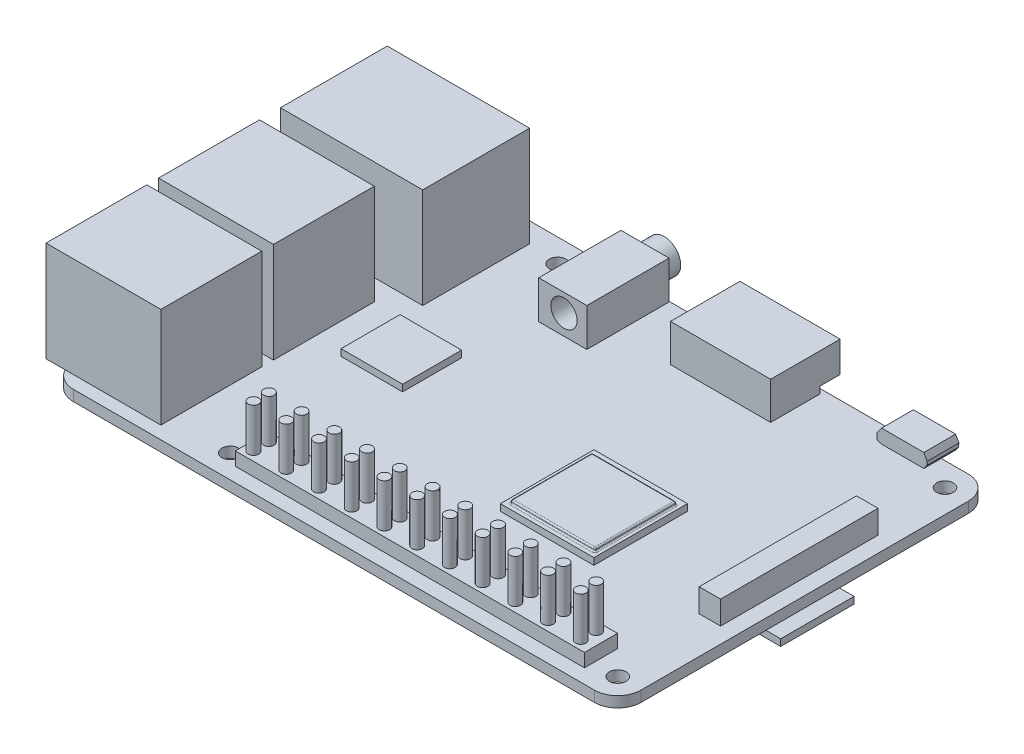
SolidWorks part; units mm, degrees
ref_plane "Front Plane" through (0, 0, 0) normal (0, 0, 1) x (1, 0, 0)
ref_plane "Top Plane" through (0, 0, 0) normal (0, 1, 0) x (1, 0, 0)
ref_plane "Right Plane" through (0, 0, 0) normal (1, 0, 0) x (0, 0, -1)
sketch "Sketch1" plane through (0, 0, 0) normal (0, 1, 0) x (1, 0, 0)
  line L1 (0, 0) -> (85, 0)
  line L2 (0, 0) -> (0, 56)
  line L3 (0, 56) -> (85, 56)
  line L4 (85, 0) -> (85, 56)
  dimension "D1" = 56
  dimension "D2" = 85
extrude "Boss-Extrude1" add sketch "Sketch1" along normal blind 1.6
fillet "Fillet1" radius 3.5 4 edges at (85, 0.8, -56) (85, 0.8, 0) (0, 0.8, 0) (0, 0.8, -56)
sketch "Sketch2" plane through (0, 1.6, 0) normal (0, 1, 0) x (1, 0, 0)
  line L1 (18.8, 53.0063) -> (-2.5, 53.0063)
  line L2 (18.8, 53.0063) -> (18.8, 37.0063)
  line L3 (18.8, 37.0063) -> (-2.5, 37.0063)
  line L4 (-2.5, 53.0063) -> (-2.5, 37.0063)
  line L5 (14.7, 33.8663) -> (-2.5, 33.8663)
  line L6 (14.7, 33.8663) -> (14.7, 18.7663)
  line L7 (14.7, 18.7663) -> (-2.5, 18.7663)
  line L8 (-2.5, 33.8663) -> (-2.5, 18.7663)
  line L9 (14.7, 17.0126) -> (-2.5, 17.0126)
  line L10 (14.7, 17.0126) -> (14.7, 1.9126)
  line L11 (14.7, 1.9126) -> (-2.5, 1.9126)
  line L12 (-2.5, 17.0126) -> (-2.5, 1.9126)
  line L13 (0, 52.5) -> (0, 3.5) construction
  point P12 (9.2217, 37.0063)
  point P13 (9.3042, 1.9126)
  dimension "D1" = 16
  dimension "D2" = 3.14
  dimension "D3" = 15.1
  dimension "D4" = 15.1
  dimension "D5" = 2.5
  dimension "D6" = 2.5
  dimension "D7" = 2.5
  dimension "D8" = 21.3
  dimension "D9" = 17.2
  dimension "D10" = 17.2
extrude "Boss-Extrude2" add sketch "Sketch2" along normal blind 15
sketch "Sketch3" plane through (-2.5, 0, 0) normal (-1, 0, 0) x (0, 0, 1)
  line L0 (-45.8667, 4.3384) -> (-51.1516, 4.3384)
  line L1 (-51.1516, 14.7961) -> (-38.5002, 14.7961)
  line L2 (-51.1516, 14.7961) -> (-51.1516, 4.3384)
  line L3 (-43.0569, 4.3384) -> (-38.5002, 4.3384)
  line L4 (-38.5002, 14.7961) -> (-38.5002, 4.3384)
  line L6 (-45.8667, 4.3384) -> (-45.8667, 3.5056)
  line L7 (-45.8667, 3.5056) -> (-43.0569, 3.5056)
  line L8 (-43.0569, 4.3384) -> (-43.0569, 3.5056)
extrude "Cut-Extrude1" cut sketch "Sketch3" against normal blind 12
sketch "Sketch4" plane through (-2.5, 0, 0) normal (-1, 0, 0) x (0, 0, 1)
  line L1 (-32.1262, 7.3198) -> (-20.7974, 7.3198)
  line L2 (-32.1262, 7.3198) -> (-32.1262, 3.1429)
  line L3 (-32.1262, 3.1429) -> (-20.7974, 3.1429)
  line L4 (-20.7974, 7.3198) -> (-20.7974, 3.1429)
  line L5 (-32.0153, 14.7191) -> (-20.7974, 14.7191)
  line L6 (-32.0153, 14.7191) -> (-32.0153, 10.2087)
  line L7 (-32.0153, 10.2087) -> (-20.7974, 10.2087)
  line L8 (-20.7974, 14.7191) -> (-20.7974, 10.2087)
  line L9 (-14.8393, 14.7191) -> (-3.9221, 14.7191)
  line L10 (-14.8393, 14.7191) -> (-14.8393, 10.2087)
  line L11 (-14.8393, 10.2087) -> (-3.9221, 10.2087)
  line L12 (-3.9221, 14.7191) -> (-3.9221, 10.2087)
  line L13 (-14.5764, 7.3198) -> (-3.9221, 7.3198)
  line L14 (-14.5764, 7.3198) -> (-14.5764, 3.1429)
  line L15 (-14.5764, 3.1429) -> (-3.9221, 3.1429)
  line L16 (-3.9221, 7.3198) -> (-3.9221, 3.1429)
  point P16 (-32.0153, 14.7191)
  point P17 (-14.929, 14.8896)
  point P18 (-14.8393, 14.7191)
  point P19 (-3.9221, 7.3198)
  point P20 (-20.7974, 7.3198)
extrude "Cut-Extrude2" cut sketch "Sketch4" against normal blind 12
sketch "Sketch5" plane through (0, 1.6, 0) normal (0, 1, 0) x (1, 0, 0)
  line L1 (19.274, 33.143) -> (28.4891, 33.143)
  line L2 (19.274, 33.143) -> (19.274, 24.3088)
  line L3 (19.274, 24.3088) -> (28.4891, 24.3088)
  line L4 (28.4891, 33.143) -> (28.4891, 24.3088)
extrude "Boss-Extrude3" add sketch "Sketch5" along normal blind 1
sketch "Sketch6" plane through (0, 1.6, 0) normal (0, 1, 0) x (1, 0, 0)
  line L0 (85, 3.5) -> (85, 52.5) construction
  line L1 (60, 47.9) -> (45, 47.9)
  line L2 (60, 47.9) -> (60, 58.3)
  line L3 (60, 58.3) -> (45, 58.3)
  line L4 (45, 47.9) -> (45, 58.3)
  line L5 (81.5, 56) -> (3.5, 56) construction
  dimension "D1" = 40
  dimension "D2" = 15
  dimension "D3" = 2.3
  dimension "D4" = 10.4
extrude "Boss-Extrude4" add sketch "Sketch6" along normal blind 5.6
sketch "Sketch8" plane through (0, 1.6, 0) normal (0, 1, 0) x (1, 0, 0)
  line L1 (51.3008, 30.1415) -> (65.3008, 30.1415)
  line L2 (51.3008, 30.1415) -> (51.3008, 16.1415)
  line L3 (51.3008, 16.1415) -> (65.3008, 16.1415)
  line L4 (65.3008, 30.1415) -> (65.3008, 16.1415)
  dimension "D1" = 14
  dimension "D2" = 14
extrude "Boss-Extrude5" add sketch "Sketch8" along normal blind 1
sketch "Sketch9" plane through (0, 0, -58.3) normal (0, 0, -1) x (-1, 0, 0)
  line L0 (-60, 1.6) -> (-45, 1.6)
  line L1 (-60, 1.6) -> (-45, 1.6) construction
  line L2 (-45, 1.6) -> (-45, 2.6627)
  line L3 (-45, 7.2) -> (-45, 1.6) construction
  line L4 (-45, 2.6627) -> (-45.5313, 2.1313)
  line L5 (-45.5313, 2.1313) -> (-59.5164, 2.1313)
  line L6 (-59.5164, 2.1313) -> (-60, 2.615)
  line L7 (-60, 7.2) -> (-60, 1.6) construction
  line L8 (-60, 2.615) -> (-60, 1.6)
extrude "Cut-Extrude5" cut sketch "Sketch9" against normal blind 3
sketch "Sketch10" plane through (0, 0, -58.3) normal (0, 0, -1) x (-1, 0, 0)
  line L0 (-59.6001, 6.695) -> (-45.3941, 6.695)
  line L1 (-45.3941, 6.695) -> (-45.3941, 2.9073)
  line L2 (-45.3941, 2.9073) -> (-45.8714, 2.43)
  line L3 (-45.8714, 2.43) -> (-59.1227, 2.43)
  line L4 (-59.1227, 2.43) -> (-59.6001, 2.9073)
  line L5 (-59.6001, 2.9073) -> (-59.6001, 6.695)
  point P2 (0, 0)
extrude "Cut-Extrude6" cut sketch "Sketch10" against normal blind 8
sketch "Sketch11" plane through (0, 0, -50.3) normal (0, 0, -1) x (-1, 0, 0)
  line L1 (-58.676, 5.361) -> (-46.2488, 5.361)
  line L2 (-58.676, 5.361) -> (-58.676, 4.1859)
  line L3 (-58.676, 4.1859) -> (-46.2488, 4.1859)
  line L4 (-46.2488, 5.361) -> (-46.2488, 4.1859)
  point P4 (-46.2488, 5.361)
  point P5 (0, 0)
extrude "Boss-Extrude6" add sketch "Sketch11" along normal blind 8
sketch "Sketch12" plane through (0, 2.6, 0) normal (0, 1, 0) x (1, 0, 0)
  line L1 (64.6535, 16.9241) -> (52.0403, 16.9241)
  line L2 (64.6535, 16.9241) -> (64.6535, 29.11)
  line L3 (64.6535, 29.11) -> (52.0403, 29.11)
  line L4 (52.0403, 16.9241) -> (52.0403, 29.11)
  point P4 (64.6393, 29.3773)
  point P5 (0, 0)
  point P6 (64.2875, 16.9241)
  point P7 (0, 0)
  point P8 (64.6535, 29.11)
extrude "Boss-Extrude7" add sketch "Sketch12" along normal blind 0.5
fillet "Fillet3" radius 0.2 12 edges at (64.6535, 2.6, -23.017) (64.6535, 2.85, -29.11) (58.3469, 2.6, -29.11) (52.0403, 2.85, -29.11) (52.0403, 2.6, -23.017) (52.0403, 2.85, -16.9241) (64.6535, 2.85, -16.9241) (58.3469, 2.6, -16.9241) (58.3469, 3.1, -16.9241) (52.0403, 3.1, -23.017) (58.3469, 3.1, -29.11) (64.6535, 3.1, -23.017)
sketch "Sketch13" plane through (0, 1.6, 0) normal (0, 1, 0) x (1, 0, 0)
  line L0 (85, 3.5) -> (85, 52.5) construction
  line L1 (78.3, 53.2419) -> (70.5, 53.2419)
  line L2 (78.3, 53.2419) -> (78.3, 58)
  line L3 (78.3, 58) -> (70.5, 58)
  line L4 (70.5, 53.2419) -> (70.5, 58)
  line L5 (81.5, 56) -> (3.5, 56) construction
  dimension "D1" = 7.8
  dimension "D2" = 14.5
  dimension "D3" = 2
extrude "Boss-Extrude8" add sketch "Sketch13" along normal blind 2.5
sketch "Sketch14" plane through (0, 0, -58) normal (0, 0, -1) x (-1, 0, 0)
  line L0 (-78.0828, 2.9313) -> (-77.5883, 3.8329)
  line L1 (-77.5883, 3.8329) -> (-71.2708, 3.8329)
  line L2 (-71.2708, 3.8329) -> (-70.6143, 2.9313)
  line L3 (-70.6143, 2.9313) -> (-70.6143, 1.9851)
  line L4 (-70.6143, 1.9851) -> (-71.2708, 1.7507)
  line L5 (-71.2708, 1.7507) -> (-77.5883, 1.7507)
  line L6 (-77.5883, 1.7507) -> (-78.0171, 2.3396)
  line L7 (-78.0171, 2.3396) -> (-78.0828, 2.9313)
  line L8 (-78.3, 4.1) -> (-70.5, 4.1)
  line L9 (-70.5, 4.1) -> (-70.5, 1.6)
  line L10 (-70.5, 1.6) -> (-78.3, 1.6)
  line L11 (-78.3, 1.6) -> (-78.3, 4.1)
extrude "Cut-Extrude7" cut sketch "Sketch14" against normal up to next
sketch "Sketch15" plane through (0, 0, -58) normal (0, 0, -1) x (-1, 0, 0)
  line L1 (-77.2141, 3.1124) -> (-71.4762, 3.1124)
  line L2 (-77.2141, 3.1124) -> (-77.2141, 2.2105)
  line L3 (-77.2141, 2.2105) -> (-71.4762, 2.2105)
  line L4 (-71.4762, 3.1124) -> (-71.4762, 2.2105)
extrude "Cut-Extrude8" cut sketch "Sketch15" against normal blind 2.5
sketch "Sketch16" plane through (0, 0, 0) normal (0, -1, 0) x (1, 0, 0)
  line L0 (85, -3.5) -> (85, -52.5) construction
  line L1 (78.3416, -33.2) -> (87.2, -33.2)
  line L2 (78.3416, -33.2) -> (78.3416, -22.2)
  line L3 (78.3416, -22.2) -> (87.2, -22.2)
  line L4 (87.2, -33.2) -> (87.2, -22.2)
  line L5 (81.5, -56) -> (3.5, -56) construction
  dimension "D1" = 11
  dimension "D2" = 2.2
  dimension "D3" = 33.8
extrude "Boss-Extrude9" add sketch "Sketch16" along normal blind 1
sketch "Sketch17" plane through (0, 1.6, 0) normal (0, 1, 0) x (1, 0, 0)
  line L0 (81.5, 56) -> (3.5, 56) construction
  line L1 (36.7809, 43.6) -> (29.5809, 43.6)
  line L2 (36.7809, 43.6) -> (36.7809, 58.6)
  line L3 (36.7809, 58.6) -> (29.5809, 58.6)
  line L4 (29.5809, 43.6) -> (29.5809, 58.6)
  dimension "D1" = 7.2
  dimension "D2" = 15
  dimension "D3" = 2.6
extrude "Boss-Extrude10" add sketch "Sketch17" along normal blind 5.7
sketch "Sketch18" plane through (0, 0, -58.6) normal (0, 0, -1) x (-1, 0, 0)
  line L1 (-36.7809, 7.3) -> (-29.5809, 7.3)
  line L2 (-36.7809, 7.3) -> (-36.7809, 1.6)
  line L3 (-36.7809, 1.6) -> (-29.5809, 1.6)
  line L4 (-29.5809, 7.3) -> (-29.5809, 1.6)
  circle A0 centre (-33.3518, 4.5516) radius 2.4837
  point P8 (-33.2776, 4.8438)
  point P9 (-33.3518, 4.5516)
extrude "Cut-Extrude9" cut sketch "Sketch18" against normal blind 2.7
sketch "Sketch19" plane through (0, 0, -58.6) normal (0, 0, -1) x (-1, 0, 0)
  circle A0 centre (-33.3539, 4.6108) radius 1.9717
  point P2 (-33.3539, 4.6108)
extrude "Cut-Extrude10" cut sketch "Sketch19" against normal blind 15
sketch "Sketch20" plane through (0, 1.6, 0) normal (0, 1, 0) x (1, 0, 0)
  line L1 (79.4418, 17.7484) -> (82.658, 17.7484)
  line L2 (79.4418, 17.7484) -> (79.4418, 41.3101)
  line L3 (79.4418, 41.3101) -> (82.658, 41.3101)
  line L4 (82.658, 17.7484) -> (82.658, 41.3101)
  point P4 (82.658, 41.3101)
  point P6 (85, 40.4192)
  point P7 (79.4418, 41.7266)
  point P8 (0, 0)
extrude "Boss-Extrude11" add sketch "Sketch20" along normal blind 3.5
sketch "Sketch21" plane through (0, 1.6, 0) normal (0, 1, 0) x (1, 0, 0)
  line L1 (25.6119, 7.0948) -> (77.877, 7.0948)
  line L2 (25.6119, 7.0948) -> (25.6119, 2.1418)
  line L3 (25.6119, 2.1418) -> (77.877, 2.1418)
  line L4 (77.877, 7.0948) -> (77.877, 2.1418)
extrude "Boss-Extrude12" add sketch "Sketch21" along normal blind 2
sketch "Sketch26" plane through (0, 3.6, 0) normal (0, 1, 0) x (1, 0, 0)
  circle A0 centre (27.0075, 5.7719) radius 0.7854
  circle A1 centre (31.9075, 5.7719) radius 0.7854
  circle A2 centre (36.8075, 5.7719) radius 0.7854
  circle A3 centre (41.7075, 5.7719) radius 0.7854
  circle A4 centre (46.6075, 5.7719) radius 0.7854
  circle A5 centre (51.5075, 5.7719) radius 0.7854
  circle A6 centre (56.4075, 5.7719) radius 0.7854
  circle A7 centre (61.3075, 5.7719) radius 0.7854
  circle A8 centre (66.2075, 5.7719) radius 0.7854
  circle A9 centre (71.1075, 5.7719) radius 0.7854
  circle A10 centre (76.0075, 5.7719) radius 0.7854
  circle A11 centre (31.9075, 3.4719) radius 0.7854
  circle A12 centre (36.8075, 3.4719) radius 0.7854
  circle A13 centre (41.7075, 3.4719) radius 0.7854
  circle A14 centre (46.6075, 3.4719) radius 0.7854
  circle A15 centre (51.5075, 3.4719) radius 0.7854
  circle A16 centre (56.4075, 3.4719) radius 0.7854
  circle A17 centre (61.3075, 3.4719) radius 0.7854
  circle A18 centre (66.2075, 3.4719) radius 0.7854
  circle A19 centre (71.1075, 3.4719) radius 0.7854
  circle A20 centre (76.0075, 3.4719) radius 0.7854
  circle A21 centre (27.0075, 3.4719) radius 0.7854
  dimension "D1" = 11
  dimension "D2" = 2
extrude "Boss-Extrude14" add sketch "Sketch26" along normal blind 6.5
sketch "Sketch27" plane through (0, 1.6, 0) normal (0, 1, 0) x (1, 0, 0)
  line L0 (85, 3.5) -> (85, 52.5) construction
  circle A0 centre (81.5, 3.5) radius 1.25
  circle A1 centre (81.5, 52.5) radius 1.25
  circle A2 centre (23.5, 52.5) radius 1.25
  circle A3 centre (23.5, 3.5) radius 1.25
  point P12 (23.5, 5.3381)
  point P13 (23.5, 3.5)
  point P14 (23.5, 52.5)
  dimension "D1" = 2.5
  dimension "D2" = 2.5
  dimension "D3" = 2.5
  dimension "D4" = 2.5
  dimension "D8" = 61.5
  dimension "D9" = 61.5
extrude "Cut-Extrude11" cut sketch "Sketch27" against normal blind 3
